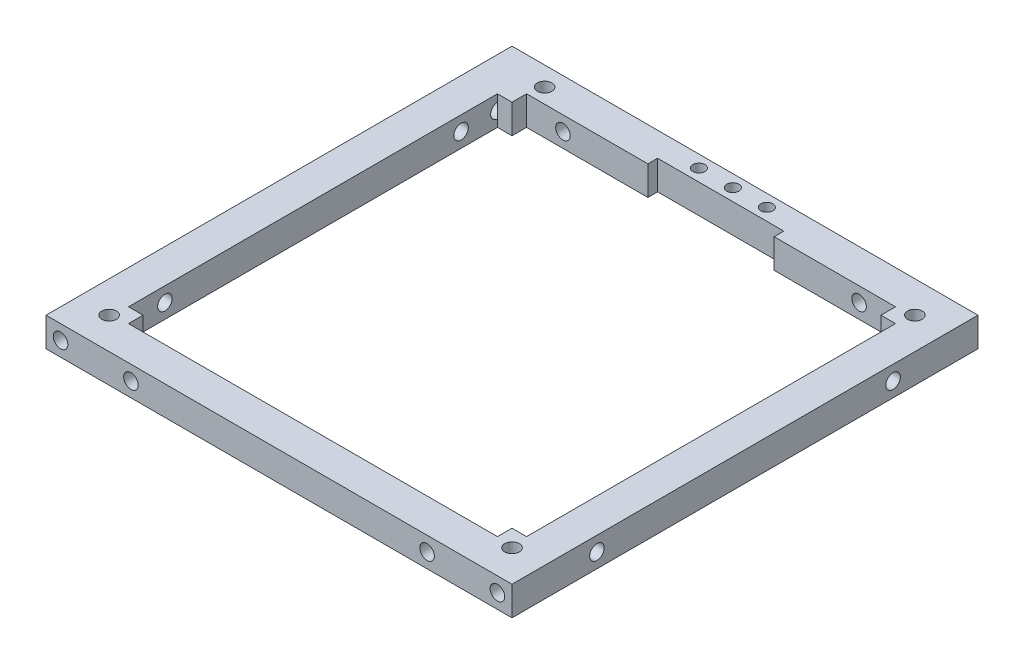
SolidWorks part; units mm, degrees
material "Aluminum"
ref_plane "Front Plane" through (0, 0, 0) normal (0, 0, 1) x (1, 0, 0)
ref_plane "Top Plane" through (0, 0, 0) normal (0, 1, 0) x (1, 0, 0)
ref_plane "Right Plane" through (0, 0, 0) normal (1, 0, 0) x (0, 0, -1)
sketch "Sketch1" plane through (0, 0, 0) normal (0, 1, 0) x (1, 0, 0)
  line L1 (48, -48) -> (-48, -48)
  line L2 (48, -48) -> (48, 48)
  line L3 (48, 48) -> (-48, 48)
  line L4 (-48, -48) -> (-48, 48)
  line L5 (48, -48) -> (-48, 48) construction
  line L6 (48, 48) -> (-48, -48) construction
  line L7 (40, -40) -> (-40, -40)
  line L8 (40, -40) -> (40, 40)
  line L9 (40, 40) -> (-40, 40)
  line L10 (-40, -40) -> (-40, 40)
  line L11 (40, -40) -> (-40, 40) construction
  line L12 (40, 40) -> (-40, -40) construction
  point P0 (0, 0)
  point P6 (0, 0)
  dimension "D1" = 96
  dimension "D2" = 96
  dimension "D3" = 8
extrude "Boss-Extrude1" add sketch "Sketch1" along normal blind 8
hole_wizard "Ø3.0 (3) Diameter Hole6" positions "Sketch8" profile "Sketch7" hole size "Ø3.0" standard "ANSI Metric"
sketch "Sketch8" plane through (0, 0, 48) normal (0, 0, 1) x (1, 0, 0)
  line L0 (-48, 8) -> (-48, 0) construction
  line L1 (48, 8) -> (48, 0) construction
  point P0 (45, 4)
  point P2 (-45, 4)
  dimension "D1" = 3
  dimension "D2" = 3
sketch "Sketch7" plane through (45, 4, 48) normal (1, 0, 0) x (0, -1, 0)
  line L0 (0, 0) -> (0, 6)
  line L1 (0, 6) -> (1.5, 6)
  line L2 (1.5, 6) -> (1.5, 0)
  line L5 (1.5, 0) -> (0, 0)
  line L10 (0, 6) -> (-1.5, 6) construction
  line L11 (0, -6.35) -> (0, 107.95) construction
  dimension "Hole Dia." = 3
  dimension "Hole Depth" = 6
  dimension "Drill Angle" = 180
hole_wizard "Ø3.0 (3) Diameter Hole3" positions "Sketch10" profile "Sketch9" hole size "Ø3.0" standard "ANSI Metric"
sketch "Sketch10" plane through (0, 0, -48) normal (0, 0, -1) x (-1, 0, 0)
  line L0 (48, 8) -> (48, 0) construction
  line L1 (-48, 8) -> (-48, 0) construction
  point P0 (-45, 4)
  point P2 (45, 4)
  dimension "D1" = 3
  dimension "D2" = 3
sketch "Sketch9" plane through (45, 4, -48) normal (1, 0, 0) x (0, 1, 0)
  line L0 (0, 0) -> (0, 6)
  line L1 (0, 6) -> (1.5, 6)
  line L2 (1.5, 6) -> (1.5, 0)
  line L5 (1.5, 0) -> (0, 0)
  line L10 (0, 6) -> (-1.5, 6) construction
  line L11 (0, -6.35) -> (0, 107.95) construction
  dimension "Hole Dia." = 3
  dimension "Hole Depth" = 6
  dimension "Drill Angle" = 180
sketch "Sketch27" plane through (0, 8, 0) normal (0, 1, 0) x (1, 0, 0)
  line L0 (-40, 40) -> (-40, -40) construction
  line L1 (41, -41) -> (-41, -41)
  line L2 (41, -41) -> (41, 41)
  line L3 (41, 41) -> (-41, 41)
  line L4 (-41, -41) -> (-41, 41)
  line L5 (41, -41) -> (-41, 41) construction
  line L6 (41, 41) -> (-41, -41) construction
  line L7 (40, 40) -> (-40, 40) construction
  point P0 (0, 0)
  dimension "D1" = 1
  dimension "D2" = 1
extrude "Cut-Extrude2" cut sketch "Sketch27" against normal blind 10
hole_wizard "Ø3.0 (3) Diameter Hole1" positions "Sketch30" profile "Sketch29" hole size "Ø3.0" standard "ANSI Metric" end condition through all
sketch "Sketch30" plane through (0, 0, 48) normal (0, 0, 1) x (1, 0, 0)
  line L0 (-48, 8) -> (48, 8) construction
  line L1 (-48, 8) -> (-48, 0) construction
  line L2 (48, 8) -> (48, 0) construction
  point P0 (-30.5, 4)
  point P4 (30.5, 4)
  dimension "D1" = 4
  dimension "D3" = 4
  dimension "D4" = 17.5
  dimension "D5" = 17.5
sketch "Sketch29" plane through (-30.5, 4, 48) normal (1, 0, 0) x (0, -1, 0)
  line L0 (0, 0) -> (0, 96)
  line L1 (0, 96) -> (1.5, 96)
  line L2 (1.5, 96) -> (1.5, 0)
  line L5 (1.5, 0) -> (0, 0)
  line L11 (0, -6.35) -> (0, 107.95) construction
  dimension "Thru Hole Dia." = 3
  dimension "Thru Hole Depth" = 96
hole_wizard "Ø3.0 (3) Diameter Hole2" positions "Sketch32" profile "Sketch31" hole size "Ø3.0" standard "ANSI Metric" end condition through all
sketch "Sketch32" plane through (-48, 0, 0) normal (-1, 0, 0) x (0, 0, 1)
  line L2 (48, 0) -> (-48, 0) construction
  point P0 (-30.5, 4)
  point P4 (30.5, 4)
  dimension "D3" = 4
  dimension "D4" = 4
sketch "Sketch31" plane through (-48, 4, -30.5) normal (0, 1, 0) x (0, 0, 1)
  line L0 (0, 0) -> (0, 96)
  line L1 (0, 96) -> (1.5, 96)
  line L2 (1.5, 96) -> (1.5, 0)
  line L5 (1.5, 0) -> (0, 0)
  line L11 (0, -6.35) -> (0, 107.95) construction
  dimension "Thru Hole Dia." = 3
  dimension "Thru Hole Depth" = 96
sketch "Sketch35" plane through (0, 8, 0) normal (0, 1, 0) x (1, 0, 0)
  line L0 (0, 0) -> (0, 22.3578) construction
  line L1 (-41, 41) -> (-38, 41)
  line L2 (-41, 41) -> (-41, 38)
  line L3 (-41, 38) -> (-38, 38)
  line L4 (-38, 41) -> (-38, 38)
  line L5 (0, 0) -> (17.564, 0) construction
  line L6 (38, 41) -> (38, 38)
  line L7 (41, 38) -> (38, 38)
  line L8 (41, 41) -> (41, 38)
  line L9 (41, 41) -> (38, 41)
  line L10 (41, -41) -> (38, -41)
  line L11 (41, -41) -> (41, -38)
  line L12 (41, -38) -> (38, -38)
  line L13 (38, -41) -> (38, -38)
  line L14 (-38, -41) -> (-38, -38)
  line L15 (-41, -38) -> (-38, -38)
  line L16 (-41, -41) -> (-41, -38)
  line L17 (-41, -41) -> (-38, -41)
  line M30 (41, 41) -> (41, -41)
  line M31 (41, -41) -> (-41, -41)
  dimension "D1" = 3
  dimension "D2" = 3
extrude "Boss-Extrude2" add sketch "Sketch35" against normal blind 8 contours L13 L12 M31 M30 | L3 L4 L1 L2 | L7 L6 L9 L8 | L15 L14 L17 L16
hole_wizard "Ø3.0 (3) Diameter Hole7" positions "Sketch42" profile "Sketch41" hole size "Ø3.0" standard "ANSI Metric" end condition through all
sketch "Sketch42" plane through (0, 8, 0) normal (0, 1, 0) x (1, 0, 0)
  line L0 (48, 48) -> (-48, 48) construction
  line L1 (48, -48) -> (48, 48) construction
  line L2 (-48, -48) -> (48, -48) construction
  line L4 (-48, 48) -> (-48, -48) construction
  point P0 (-37.33, 44.05)
  point P3 (41.5, 41.5)
  point P6 (41.5, -41.5)
  point P9 (-41.5, -41.5)
  dimension "D3" = 6.5
  dimension "D4" = 6.5
  dimension "D5" = 6.5
  dimension "D6" = 6.5
sketch "Sketch41" plane through (-37.33, 8, -44.05) normal (1, 0, 0) x (0, 0, 1)
  line L0 (0, 0) -> (0, 8)
  line L1 (0, 8) -> (1.5, 8)
  line L2 (1.5, 8) -> (1.5, 0)
  line L5 (1.5, 0) -> (0, 0)
  line L11 (0, -6.35) -> (0, 107.95) construction
  dimension "Thru Hole Dia." = 3
  dimension "Thru Hole Depth" = 8
sketch "Sketch44" plane through (0, 0, -48) normal (0, 0, -1) x (-1, 0, 0)
  line L0 (48, 8) -> (48, 0) construction
  line L1 (-48, 8) -> (48, 8)
  line L2 (-48, 8) -> (-48, 7)
  line L3 (-48, 7) -> (48, 7)
  line L4 (48, 8) -> (48, 7)
  line L5 (-48, 8) -> (48, 8) construction
  line L6 (-48, 0) -> (48, 0) construction
  line L7 (48, 0) -> (-48, 0)
  line L8 (48, 0) -> (48, 1)
  line L9 (48, 1) -> (-48, 1)
  line L10 (-48, 0) -> (-48, 1)
  line L11 (-48, 8) -> (-48, 0) construction
  dimension "D1" = 1
  dimension "D2" = 1
extrude "Cut-Extrude4" cut sketch "Sketch44" against normal blind 142
sketch "Sketch47" plane through (0, 7, 0) normal (0, 1, 0) x (1, 0, 0)
  line L0 (38, 41) -> (-38, 41) construction
  line L1 (-7, 43) -> (7, 43)
  line L2 (-7, 43) -> (-7, 41)
  line L3 (-7, 41) -> (7, 41)
  line L4 (7, 43) -> (7, 41)
  line L5 (0, 48.3118) -> (0, 66.2942) construction
  dimension "D1" = 7
  dimension "14" = 14
  dimension "D2" = 2
extrude "Cut-Extrude5" cut sketch "Sketch47" against normal blind 10
hole_wizard "Ø2.5 (2.5) Diameter Hole1" positions "Sketch49" profile "Sketch48" hole size "Ø2.5" standard "ANSI Metric" end condition through all
sketch "Sketch49" plane through (0, 1, 0) normal (0, -1, 0) x (-1, 0, 0)
  point P0 (7, 45.5)
  point P2 (0, 45.5)
  point P4 (-7, 45.5)
  dimension "D1" = 7
  dimension "D2" = 7
sketch "Sketch48" plane through (-7, 1, -45.5) normal (1, 0, 0) x (0, 0, -1)
  line L0 (0, 0) -> (0, 6)
  line L1 (0, 6) -> (1.25, 6)
  line L2 (1.25, 6) -> (1.25, 0)
  line L5 (1.25, 0) -> (0, 0)
  line L11 (0, -6.35) -> (0, 107.95) construction
  dimension "Thru Hole Dia." = 2.5
  dimension "Thru Hole Depth" = 6
hole_wizard "Tap Drill for M3x0.5 Tap3" positions "Sketch53" profile "Sketch52" hole size "M3x0.5" standard "ANSI Metric"
sketch "Sketch53" plane through (-48, 0, 0) normal (-1, 0, 0) x (0, 0, 1)
  line L0 (48, 7) -> (-48, 7) construction
  line L1 (0, 7) -> (0, -29.6854) construction
  point P0 (38.1, 4)
  point P2 (-38.1, 4)
  dimension "D1" = 38.1
  dimension "D2" = 38.1
sketch "Sketch52" plane through (-48, 4, 38.1) normal (0, 1, 0) x (0, 0, 1)
  line L0 (0, 0) -> (0, 7)
  line L1 (0, 7) -> (1.5, 7)
  line L2 (1.5, 7) -> (1.5, 0)
  line L5 (1.5, 0) -> (0, 0)
  line L10 (0, 7) -> (-1.5, 7) construction
  line L11 (0, -6.35) -> (0, 107.95) construction
  dimension "Hole Dia." = 3
  dimension "Hole Depth" = 7
  dimension "Drill Angle" = 180
sketch "Sketch54" plane through (0, 0, -41) normal (0, 0, 1) x (1, 0, 0)
  line L1 (-7, 7) -> (-13, 7)
  line L2 (-7, 7) -> (-7, 1)
  line L3 (-7, 1) -> (-13, 1)
  line L4 (-13, 7) -> (-13, 1)
  line L5 (7, 7) -> (13, 7)
  line L6 (7, 7) -> (7, 1)
  line L7 (7, 1) -> (13, 1)
  line L8 (13, 7) -> (13, 1)
  dimension "D1" = 6
  dimension "D2" = 6
  dimension "D3" = 6
  dimension "D4" = 6
extrude "Cut-Extrude6" cut sketch "Sketch54" against normal blind 2
